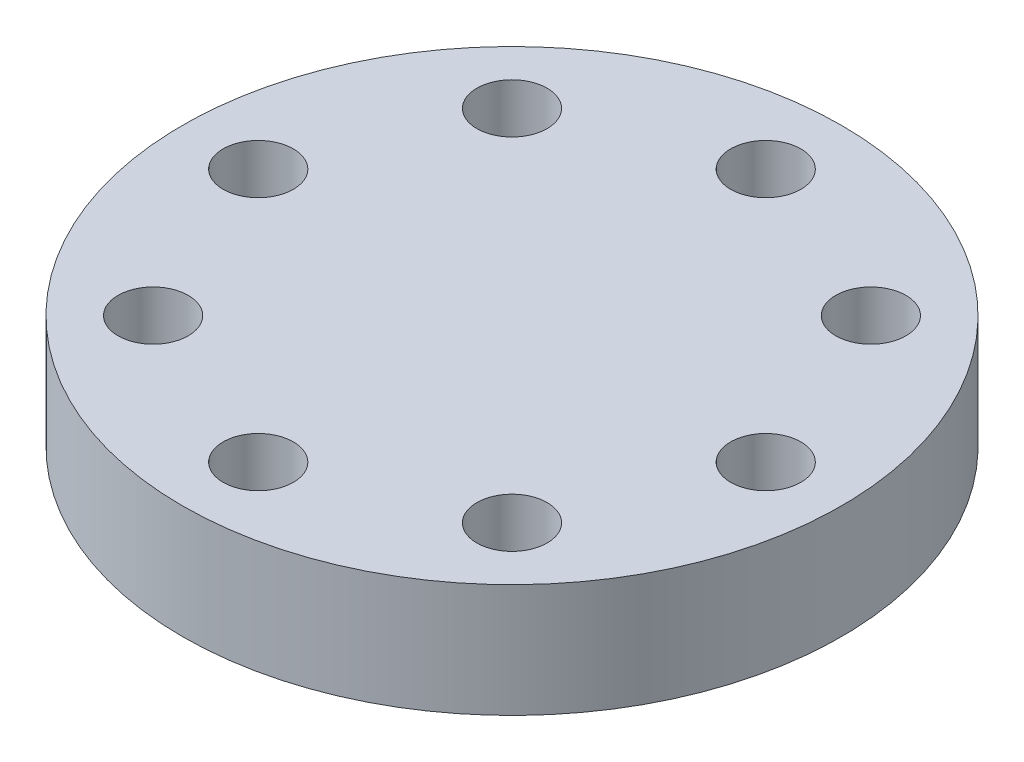
SolidWorks part; units mm, degrees
ref_plane "Front Plane" through (0, 0, 0) normal (0, 0, 1) x (1, 0, 0)
ref_plane "Top Plane" through (0, 0, 0) normal (0, 1, 0) x (1, 0, 0)
ref_plane "Right Plane" through (0, 0, 0) normal (1, 0, 0) x (0, 0, -1)
sketch "Sketch1" plane through (0, 0, 0) normal (0, 1, 0) x (1, 0, 0)
  circle A0 centre (0, 0) radius 12.7
  dimension "D1" = 25.4
extrude "Boss-Extrude1" add sketch "Sketch1" along normal blind 4.3656
sketch "Sketch2" plane through (0, 4.3656, 0) normal (0, 1, 0) x (1, 0, 0)
  point P0 (0, 9.779)
  point P1 (6.9148, 6.9148)
  point P5 (9.779, 0)
  point P6 (6.9148, -6.9148)
  point P7 (0, -9.779)
  point P8 (-6.9148, -6.9148)
  point P9 (-9.779, 0)
  point P10 (-6.9148, 6.9148)
  point P11 (0, 0)
  dimension "D1" = 9.779
  dimension "D2" = 8
hole_wizard "#6-32 Tapped Hole1" positions "Sketch4" profile "Sketch3" tap size "#6-32" standard "ANSI Inch"
sketch "Sketch4" plane through (0, 4.3656, 0) normal (0, 1, 0) x (1, 0, 0)
  point P0 (0, 9.779)
  point P3 (6.9148, 6.9148)
  point P6 (9.779, 0)
  point P9 (6.9148, -6.9148)
  point P12 (0, -9.779)
  point P15 (-6.9148, -6.9148)
  point P18 (-9.779, 0)
  point P21 (-6.9148, 6.9148)
sketch "Sketch3" plane through (0, 4.3656, -9.779) normal (1, 0, 0) x (0, 0, 1)
  line L0 (0, 0) -> (0, 24.6887)
  line L1 (0, 24.6887) -> (1.3525, 23.876)
  line L2 (1.3525, 23.876) -> (1.3525, 0)
  line L5 (1.3525, 0) -> (0, 0)
  line L10 (0, 24.6887) -> (-1.3525, 23.876) construction
  line L11 (0, -6.35) -> (0, 107.95) construction
  dimension "Tap Drill Dia." = 2.7051
  dimension "Tap Drill Depth" = 23.876
  dimension "Drill Angle" = 118
cosmetic thread "Hole Thread1"
cosmetic thread "Hole Thread2"
cosmetic thread "Hole Thread3"
cosmetic thread "Hole Thread4"
cosmetic thread "Hole Thread5"
cosmetic thread "Hole Thread6"
cosmetic thread "Hole Thread7"
cosmetic thread "Hole Thread8"
